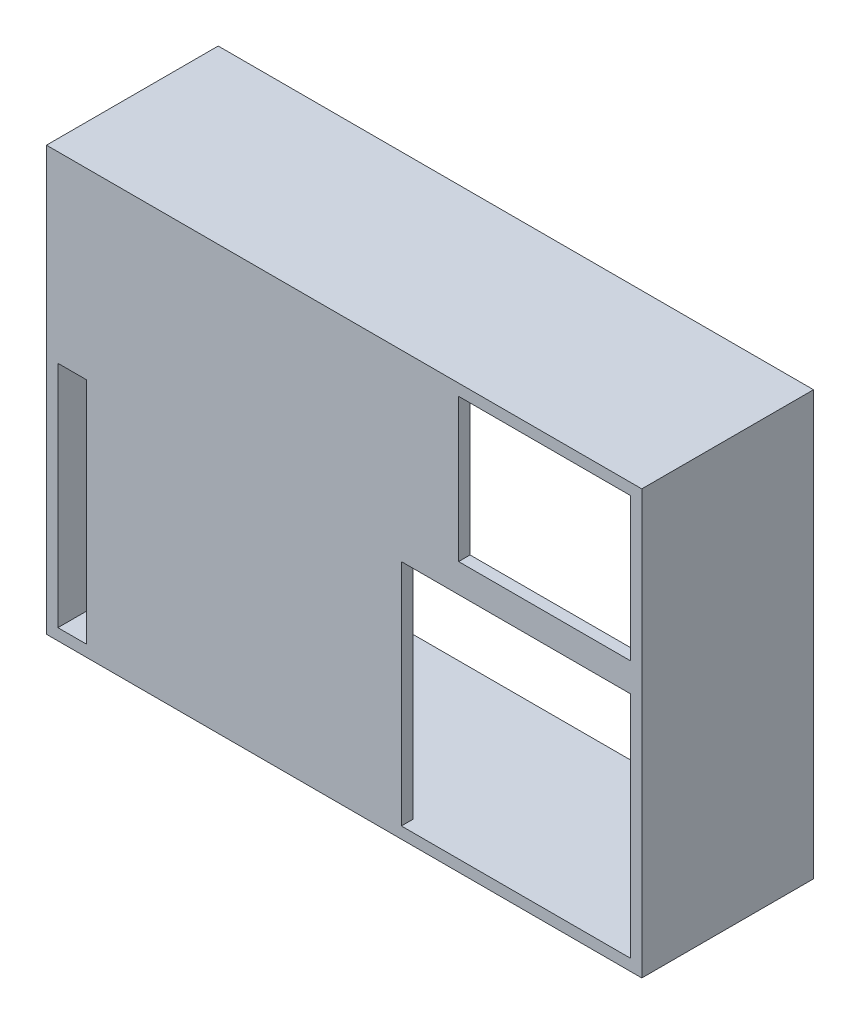
SolidWorks part; units mm, degrees
ref_plane "Front Plane" through (0, 0, 0) normal (0, 0, 1) x (1, 0, 0)
ref_plane "Top Plane" through (0, 0, 0) normal (0, 1, 0) x (1, 0, 0)
ref_plane "Right Plane" through (0, 0, 0) normal (1, 0, 0) x (0, 0, -1)
sketch "Sketch1" plane through (0, 0, 0) normal (0, 0, 1) x (1, 0, 0)
  line L1 (0, 0) -> (-104, 0)
  line L2 (0, 0) -> (0, 74)
  line L3 (0, 74) -> (-104, 74)
  line L4 (-104, 0) -> (-104, 74)
  line L5 (-102, 42) -> (-97, 42)
  line L6 (-102, 42) -> (-102, 2)
  line L7 (-102, 2) -> (-97, 2)
  line L8 (-97, 42) -> (-97, 2)
  line L9 (-42, 42) -> (-2, 42)
  line L10 (-42, 42) -> (-42, 2)
  line L11 (-42, 2) -> (-2, 2)
  line L12 (-2, 42) -> (-2, 2)
  line L13 (-32, 72) -> (-2, 72)
  line L14 (-32, 72) -> (-32, 47)
  line L15 (-32, 47) -> (-2, 47)
  line L16 (-2, 72) -> (-2, 47)
  dimension "D1" = 104
  dimension "D2" = 74
  dimension "D3" = 2
  dimension "D4" = 2
  dimension "D5" = 5
  dimension "D6" = 40
  dimension "D7" = 2
  dimension "D8" = 2
  dimension "D9" = 40
  dimension "D10" = 40
  dimension "D11" = 2
  dimension "D12" = 2
  dimension "D13" = 25
  dimension "D14" = 30
extrude "Boss-Extrude1" add sketch "Sketch1" along normal blind 30
sketch "Sketch2" plane through (0, 0, 0) normal (0, 0, -1) x (-1, 0, 0)
  line L0 (0, 74) -> (104, 74) construction
  line L1 (2, 72) -> (102, 72)
  line L2 (2, 72) -> (2, 2)
  line L3 (2, 2) -> (102, 2)
  line L4 (102, 72) -> (102, 2)
  line L5 (104, 0) -> (0, 0) construction
  line L6 (104, 74) -> (104, 0) construction
  line L7 (0, 0) -> (0, 74) construction
  dimension "D1" = 2
  dimension "D2" = 2
  dimension "D3" = 2
  dimension "D4" = 2
extrude "Cut-Extrude1" cut sketch "Sketch2" against normal blind 28
